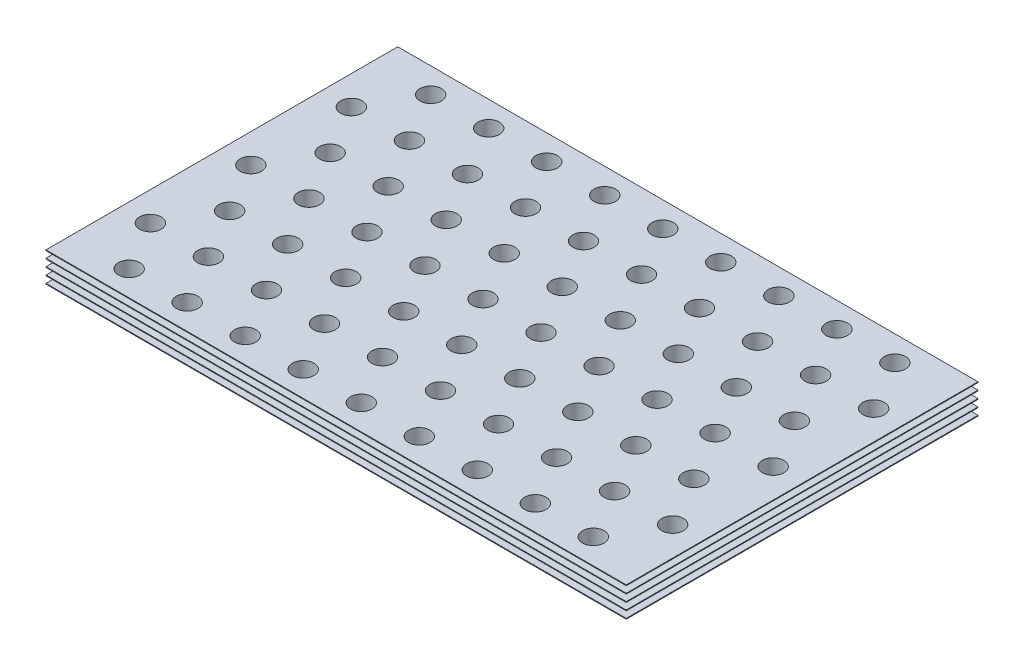
SolidWorks part; units mm, degrees
ref_plane "Front Plane" through (0, 0, 0) normal (0, 0, 1) x (1, 0, 0)
ref_plane "Top Plane" through (0, 0, 0) normal (0, 1, 0) x (1, 0, 0)
ref_plane "Right Plane" through (0, 0, 0) normal (1, 0, 0) x (0, 0, -1)
sketch "Sketch1" plane through (0, 0, 0) normal (0, 1, 0) x (1, 0, 0)
  line L1 (-127, 76.9874) -> (127, 76.9874)
  line L2 (-127, 76.9874) -> (-127, -76.9874)
  line L3 (-127, -76.9874) -> (127, -76.9874)
  line L4 (127, 76.9874) -> (127, -76.9874)
  line L5 (-127, 76.9874) -> (127, -76.9874) construction
  line L6 (-127, -76.9874) -> (127, 76.9874) construction
  point P0 (0, 0)
  dimension "D1" = 153.9748
  dimension "D2" = 254
extrude "Boss-Extrude1" add sketch "Sketch1" along normal blind 0.3302
pattern_linear "LPattern1" count 5 spacing 3.175 along (0, 1, 0) of bodies 101
sketch "Sketch2" plane through (0, 0, 0) normal (0, -1, 0) x (1, 0, 0)
  line L1 (127, 76.9874) -> (127, -76.9874) construction
  line L3 (-127, 76.9874) -> (127, 76.9874) construction
  circle A2 centre (101.6, 65.9892) radius 5.1054
  circle A3 centre (114.3, 43.9928) radius 5.1054 construction
  dimension "D1" = 10.2108
  dimension "D2" = 10.2108
  dimension "D3" = 25.4
  dimension "D4" = 10.9982
  dimension "D5" = 32.9946
  dimension "D6" = 12.7
extrude "Boss-Extrude2" add sketch "Sketch2" against normal up to surface (13.0302 mm away)
sketch "Sketch3" plane through (0, 0, 0) normal (0, -1, 0) x (1, 0, 0)
  circle A6 centre (101.6, 65.9892) radius 4.7085
  circle A7 centre (101.6, 65.9892) radius 4.7085
  dimension "D1" = 0.3969
extrude "Cut-Extrude1" cut sketch "Sketch3" against normal through all both and the other way through all
pattern_linear "LPattern2" count 9 spacing 25.4 along (-1, 0, 0) count 4 spacing 43.9928 along (0, 0, -1) of "Boss-Extrude2"
pattern_linear "LPattern3" count 9 spacing 25.4 along (-1, 0, 0) count 4 spacing 43.9928 along (0, 0, -1) of "Cut-Extrude1"
sketch "Sketch4" plane through (0, 0, 0) normal (0, -1, 0) x (1, 0, 0)
  circle A0 centre (114.3, 43.9928) radius 5.1054 construction
  circle A1 centre (114.3, 43.9928) radius 5.1054
extrude "Boss-Extrude3" add sketch "Sketch4" against normal up to surface (13.0302 mm away)
sketch "Sketch5" plane through (0, 0, 0) normal (0, -1, 0) x (1, 0, 0)
  circle A2 centre (114.3, 43.9928) radius 4.7085
  circle A3 centre (114.3, 43.9928) radius 4.7085
  dimension "D1" = 0.3969
extrude "Cut-Extrude2" cut sketch "Sketch5" against normal through all
pattern_linear "LPattern4" count 10 spacing 25.4 along (-1, 0, 0) count 3 spacing 43.9928 along (0, 0, -1) of "Boss-Extrude3"
pattern_linear "LPattern5" count 10 spacing 25.4 along (-1, 0, 0) count 3 spacing 43.9928 along (0, 0, -1) of "Cut-Extrude2"
equation "\"D2@Sketch1\"=\"N3\"*\"X3\""
equation "\"D1@Sketch1\"=\"N1\"*\"X1\""
equation "\"N1\"= 7"
equation "\"N2\"= 5"
equation "\"N3\"= 10"
equation "\"X1\"= 0.866"
equation "\"X2\"= 0.125"
equation "\"X3\"= 1"
equation "\"D3@LPattern1\"=\"X2\""
equation "\"D3@Sketch2\"=\"X3\""
equation "\"D4@Sketch2\"=\"X1\"/2"
equation "\"D5@Sketch2\"=\"X1\"+0.5*\"X1\""
equation "\"D6@Sketch2\"=\"X3\"/2"
equation "\"D3@LPattern2\"=\"X3\""
equation "\"D1@LPattern2\"= \"N3\" - 1"
equation "\"D3@LPattern3\"=\"X3\""
equation "\"D1@LPattern3\"=\"N3\"-1"
equation "\"D3@LPattern4\"=\"X3\""
equation "\"D1@LPattern4\" = \"N3\""
equation "\"D3@LPattern5\"=\"X3\""
equation "\"D1@LPattern5\"=\"N3\""
equation "\"D4@LPattern2\"=\"X1\"*2"
equation "\"D4@LPattern3\"=\"X1\"*2"
equation "\"D2@LPattern2\"= round ( \"N1\" / 2 )"
equation "\"D2@LPattern3\"= round ( \"N1\" / 2 )"
equation "\"D4@LPattern4\"=\"X1\"*2"
equation "\"D2@LPattern4\"=int(\"N1\"/2)"
equation "\"D4@LPattern5\"=\"X1\"*2"
equation "\"D2@LPattern5\"=int(\"N1\"/2)"
